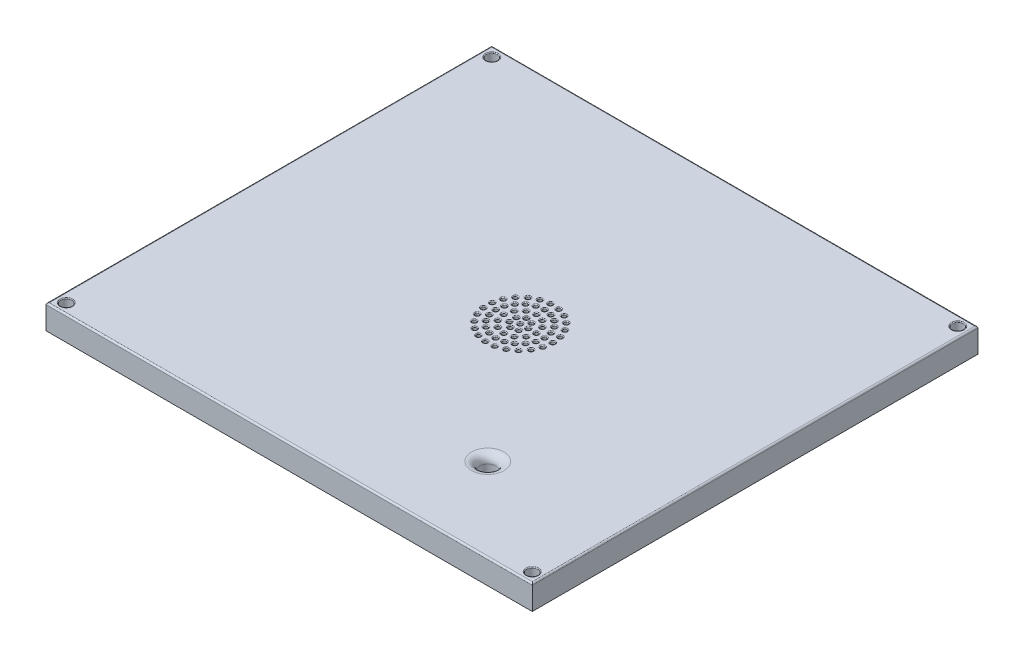
SolidWorks part; units mm, degrees
ref_plane "Front Plane" through (0, 0, 0) normal (0, 0, 1) x (1, 0, 0)
ref_plane "Top Plane" through (0, 0, 0) normal (0, 1, 0) x (1, 0, 0)
ref_plane "Right Plane" through (0, 0, 0) normal (1, 0, 0) x (0, 0, -1)
sketch "Sketch1" plane through (0, 0, 0) normal (0, 1, 0) x (1, 0, 0)
  line L1 (-76.2, -69.85) -> (76.2, -69.85)
  line L2 (-76.2, -69.85) -> (-76.2, 69.85)
  line L3 (-76.2, 69.85) -> (76.2, 69.85)
  line L4 (76.2, -69.85) -> (76.2, 69.85)
  line L5 (-76.2, -69.85) -> (76.2, 69.85) construction
  line L6 (-76.2, 69.85) -> (76.2, -69.85) construction
  point P0 (0, 0)
  dimension "D1" = 139.7
  dimension "D2" = 152.4
extrude "Boss-Extrude1" add sketch "Sketch1" along normal blind 7.62
sketch "Sketch2" plane through (0, 7.62, 0) normal (0, 1, 0) x (1, 0, 0)
  line L0 (76.2, 69.85) -> (-76.2, 69.85) construction
  line L1 (-76.2, 69.85) -> (-76.2, -69.85) construction
  line L2 (76.2, -69.85) -> (76.2, 69.85) construction
  line L3 (-76.2, -69.85) -> (76.2, -69.85) construction
  circle A0 centre (-73.025, 66.675) radius 1.7526
  circle A1 centre (73.025, 66.675) radius 1.7526
  circle A2 centre (73.025, -66.675) radius 1.7526
  circle A3 centre (-73.025, -66.675) radius 1.7526
  dimension "D1" = 3.5052
  dimension "D2" = 3.5052
  dimension "D3" = 3.5052
  dimension "D4" = 3.5052
  dimension "D5" = 3.175
  dimension "D6" = 3.175
  dimension "D7" = 3.175
  dimension "D8" = 3.175
  dimension "D9" = 3.175
  dimension "D10" = 3.175
  dimension "D11" = 3.175
  dimension "D12" = 3.175
extrude "Cut-Extrude1" cut sketch "Sketch2" against normal through all
sketch "Sketch3" plane through (0, 7.62, 0) normal (0, 1, 0) x (1, 0, 0)
  line L0 (76.2, -69.85) -> (76.2, 69.85) construction
  line L1 (-76.2, -69.85) -> (76.2, -69.85) construction
  circle A0 centre (36.068, -43.6626) radius 2.54
  dimension "D1" = 5.08
  dimension "D2" = 40.132
  dimension "D3" = 26.1874
extrude "Cut-Extrude2" cut sketch "Sketch3" against normal through all
fillet "Fillet1" radius 2.54 1 edges at (36.068, 7.62, 46.2026)
fillet "Fillet2" radius 2.54 1 edges at (36.068, 0, 46.2026)
fillet "Fillet3" radius 0.508 4 edges at (-76.2, 7.62, 0) (0, 7.62, -69.85) (76.2, 7.62, 0) (0, 7.62, 69.85)
sketch "Sketch4" plane through (0, 7.62, 0) normal (0, 1, 0) x (1, 0, 0)
  line L0 (75.692, -69.342) -> (75.692, 69.342) construction
  line L1 (-75.692, -69.342) -> (75.692, -69.342) construction
  circle A0 centre (3.81, -1.27) radius 0.635
  circle A1 centre (6.3658, -1.27) radius 0.635
  circle A2 centre (8.9216, -1.27) radius 0.635
  circle A3 centre (11.4774, -1.27) radius 0.635
  circle A4 centre (14.0332, -1.27) radius 0.635
  circle A5 centre (5.4035, -3.2682) radius 0.635
  circle A6 centre (3.2413, -3.7617) radius 0.635
  circle A7 centre (1.5073, -2.3789) radius 0.635
  circle A8 centre (1.5073, -0.1611) radius 0.635
  circle A9 centre (3.2413, 1.2217) radius 0.635
  circle A10 centre (5.4035, 0.7282) radius 0.635
  circle A11 centre (8.2368, -3.8258) radius 0.635
  circle A12 centre (6.3658, -5.6968) radius 0.635
  circle A13 centre (3.81, -6.3816) radius 0.635
  circle A14 centre (1.2542, -5.6968) radius 0.635
  circle A15 centre (-0.6168, -3.8258) radius 0.635
  circle A16 centre (-1.3016, -1.27) radius 0.635
  circle A17 centre (-0.6168, 1.2858) radius 0.635
  circle A18 centre (1.2542, 3.1568) radius 0.635
  circle A19 centre (3.81, 3.8416) radius 0.635
  circle A20 centre (6.3658, 3.1568) radius 0.635
  circle A21 centre (8.2368, 1.2858) radius 0.635
  circle A22 centre (11.1021, -3.6393) radius 0.635
  circle A23 centre (10.013, -5.7768) radius 0.635
  circle A24 centre (8.3168, -7.473) radius 0.635
  circle A25 centre (6.1793, -8.5621) radius 0.635
  circle A26 centre (3.81, -8.9374) radius 0.635
  circle A27 centre (1.4407, -8.5621) radius 0.635
  circle A28 centre (-0.6968, -7.473) radius 0.635
  circle A29 centre (-2.393, -5.7768) radius 0.635
  circle A30 centre (-3.4821, -3.6393) radius 0.635
  circle A31 centre (-3.8574, -1.27) radius 0.635
  circle A32 centre (-3.4821, 1.0993) radius 0.635
  circle A33 centre (-2.393, 3.2368) radius 0.635
  circle A34 centre (-0.6968, 4.933) radius 0.635
  circle A35 centre (1.4407, 6.0221) radius 0.635
  circle A36 centre (3.81, 6.3974) radius 0.635
  circle A37 centre (6.1793, 6.0221) radius 0.635
  circle A38 centre (8.3168, 4.933) radius 0.635
  circle A39 centre (10.013, 3.2368) radius 0.635
  circle A40 centre (11.1021, 1.0993) radius 0.635
  circle A41 centre (13.6541, -4.0282) radius 0.635
  circle A42 centre (12.5449, -6.5818) radius 0.635
  circle A43 centre (10.7878, -8.7415) radius 0.635
  circle A44 centre (8.5133, -10.347) radius 0.635
  circle A45 centre (5.89, -11.2793) radius 0.635
  circle A46 centre (3.1123, -11.4693) radius 0.635
  circle A47 centre (0.3865, -10.9029) radius 0.635
  circle A48 centre (-2.0855, -9.622) radius 0.635
  circle A49 centre (-4.1202, -7.7217) radius 0.635
  circle A50 centre (-5.5668, -5.3429) radius 0.635
  circle A51 centre (-6.3179, -2.6621) radius 0.635
  circle A52 centre (-6.3179, 0.1221) radius 0.635
  circle A53 centre (-5.5668, 2.8029) radius 0.635
  circle A54 centre (-4.1202, 5.1817) radius 0.635
  circle A55 centre (-2.0855, 7.082) radius 0.635
  circle A56 centre (0.3865, 8.3629) radius 0.635
  circle A57 centre (3.1123, 8.9293) radius 0.635
  circle A58 centre (5.89, 8.7393) radius 0.635
  circle A59 centre (8.5133, 7.807) radius 0.635
  circle A60 centre (10.7878, 6.2015) radius 0.635
  circle A61 centre (12.5449, 4.0418) radius 0.635
  circle A62 centre (13.6541, 1.4882) radius 0.635
  dimension "D1" = 1.27
  dimension "D2" = 71.882
  dimension "D3" = 68.072
  dimension "D5" = 7
  dimension "D6" = 12
  dimension "D7" = 20
  dimension "D8" = 23
extrude "Cut-Extrude3" cut sketch "Sketch4" against normal through all
fillet "Fillet4" radius 0.254 67 edges at (3.81, 7.62, 1.905) (3.81, 7.62, -3.2066) (-0.6968, 7.62, -4.298) (-2.393, 7.62, -2.6018) (-3.4821, 7.62, -0.4643) (-3.8574, 7.62, 1.905) (1.4407, 7.62, -5.3871) (-2.0855, 7.62, -6.447) (-4.1202, 7.62, -4.5467) (-5.5668, 7.62, -2.1679) (-6.3179, 7.62, 0.5129) (-6.3179, 7.62, 3.2971) (-5.5668, 7.62, 5.9779) (-3.4821, 7.62, 4.2743) (-73.025, 7.62, -64.9224) (73.025, 7.62, -64.9224) (73.025, 7.62, 68.4276) (-73.025, 7.62, 68.4276) (10.7878, 7.62, -5.5665) (8.5133, 7.62, -7.172) (8.3168, 7.62, -4.298) (12.5449, 7.62, -3.4068) (13.6541, 7.62, -0.8532) (-2.0855, 7.62, 10.257) (0.3865, 7.62, 11.5379) (12.5449, 7.62, 7.2168) (13.6541, 7.62, 4.6632) (8.5133, 7.62, 10.982) (10.7878, 7.62, 9.3765) (11.1021, 7.62, -0.4643) (10.013, 7.62, -2.6018) (3.1123, 7.62, 12.1043) (5.89, 7.62, 11.9143) (1.4407, 7.62, 9.1971) (-0.6968, 7.62, 8.108) (6.1793, 7.62, 9.1971) (3.81, 7.62, 9.5724) (10.013, 7.62, 6.4118) (8.3168, 7.62, 8.108) (8.2368, 7.62, -0.6508) (11.1021, 7.62, 4.2743) (1.2542, 7.62, 6.3318) (3.81, 7.62, 7.0166) (5.4035, 7.62, -0.0932) (6.3658, 7.62, 6.3318) (8.2368, 7.62, 4.4608) (3.2413, 7.62, 4.3967) (5.4035, 7.62, 3.9032) (8.9216, 7.62, 1.905) (6.3658, 7.62, 1.905) (14.0332, 7.62, 1.905) (11.4774, 7.62, 1.905) (-4.1202, 7.62, 8.3567) (-2.393, 7.62, 6.4118) (-0.6168, 7.62, 4.4608) (1.5073, 7.62, 3.0139) (1.5073, 7.62, 0.7961) (3.2413, 7.62, -0.5867) (6.3658, 7.62, -2.5218) (6.1793, 7.62, -5.3871) (5.89, 7.62, -8.1043) (3.81, 7.62, -5.7624) (3.1123, 7.62, -8.2943) (0.3865, 7.62, -7.7279) (1.2542, 7.62, -2.5218) (-0.6168, 7.62, -0.6508) (-1.3016, 7.62, 1.905)
